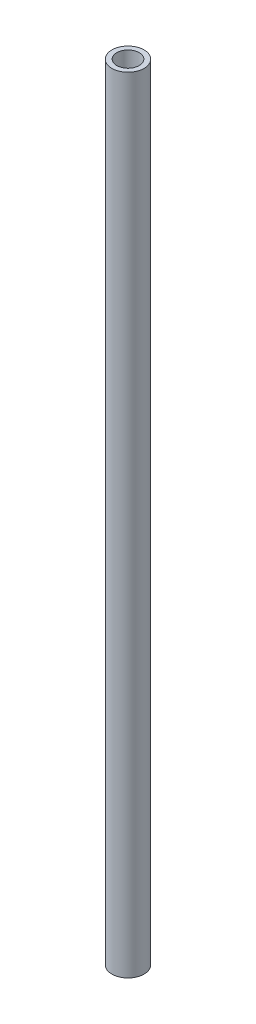
SolidWorks part; units mm, degrees
material "AISI 316 Stainless Steel Sheet (SS)"
ref_plane "Front Plane" through (0, 0, 0) normal (0, 0, 1) x (1, 0, 0)
ref_plane "Top Plane" through (0, 0, 0) normal (0, 1, 0) x (1, 0, 0)
ref_plane "Right Plane" through (0, 0, 0) normal (1, 0, 0) x (0, 0, -1)
sketch "Sketch1" plane through (0, 0, 0) normal (0, 1, 0) x (1, 0, 0)
  circle A0 centre (0, 0) radius 0.287
  circle A1 centre (0, 0) radius 0.2
  dimension "D1" = 0.574
  dimension "D2" = 0.4
extrude "Boss-Extrude1" add sketch "Sketch1" along normal blind 14
